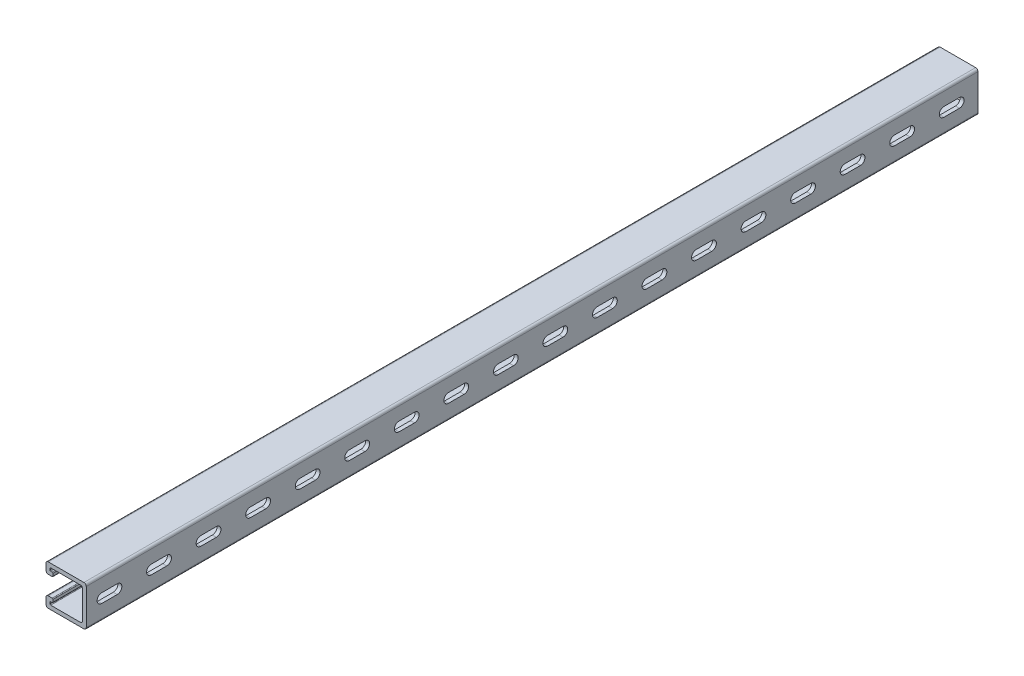
SolidWorks part; units mm, degrees
ref_plane "Front Plane" through (0, 0, 0) normal (0, 0, 1) x (1, 0, 0)
ref_plane "Top Plane" through (0, 0, 0) normal (0, 1, 0) x (1, 0, 0)
ref_plane "Right Plane" through (0, 0, 0) normal (1, 0, 0) x (0, 0, -1)
sketch "Sketch1" plane through (0, 0, 0) normal (0, 0, 1) x (1, 0, 0)
  line L0 (-13.5255, 9.525) -> (-18.2499, 9.525)
  line L1 (-20.6375, 11.9126) -> (-20.6375, 18.2499)
  line L2 (-18.2499, 20.6375) -> (18.2499, 20.6375)
  line L3 (20.6375, 18.2499) -> (20.6375, -18.2499)
  line L4 (18.2499, -20.6375) -> (-18.2499, -20.6375)
  line L5 (-20.6375, -18.2499) -> (-20.6375, -11.9126)
  line L6 (-18.2499, -9.525) -> (-13.5255, -9.525)
  line L7 (0, 0) -> (20.6375, 0) construction
  line L8 (0, 0) -> (0, 20.6375) construction
  arc A0 (-20.6375, 18.2499) -> (-18.2499, 20.6375) centre (-18.2499, 18.2499) cw
  arc A1 (-18.2499, 9.525) -> (-20.6375, 11.9126) centre (-18.2499, 11.9126) cw
  arc A2 (-20.6375, -11.9126) -> (-18.2499, -9.525) centre (-18.2499, -11.9126) cw
  arc A3 (-18.2499, -20.6375) -> (-20.6375, -18.2499) centre (-18.2499, -18.2499) cw
  arc A4 (20.6375, -18.2499) -> (18.2499, -20.6375) centre (18.2499, -18.2499) cw
  arc A5 (18.2499, 20.6375) -> (20.6375, 18.2499) centre (18.2499, 18.2499) cw
  point P14 (-20.6375, 20.6375)
  point P23 (20.6375, -20.6375)
  point P26 (20.6375, 20.6375)
  dimension "D4" = 2.3876
  dimension "D1" = 41.275
  dimension "D2" = 41.275
  dimension "D3" = 19.05
  dimension "D5" = 7.112
extrude "Extrude-Thin1" add sketch "Sketch1" against normal blind 914.4 thin
fillet "Fillet2" radius 0.762 8 edges at (-16.5735, 13.589, -457.2) (-16.5735, -16.5735, -457.2) (-16.5735, 16.5735, -457.2) (-13.5255, 13.589, -457.2) (-13.5255, 9.525, -457.2) (-13.5255, -9.525, -457.2) (-13.5255, -13.589, -457.2) (-16.5735, -13.589, -457.2)
fillet "Fillet3" radius 1.524 2 edges at (16.5735, 16.5735, -457.2) (16.5735, -16.5735, -457.2)
sketch "Sketch2" plane through (20.6375, 0, 0) normal (1, 0, 0) x (0, 0, -1)
  line L0 (15.875, 0) -> (31.75, 0) construction
  line L1 (15.875, 4.7625) -> (31.75, 4.7625)
  line L2 (15.875, -4.7625) -> (31.75, -4.7625)
  line L4 (15.875, 0) -> (0, 0) construction
  line L5 (23.8125, 0) -> (74.6125, 0) construction
  line L6 (0, 18.2499) -> (0, -18.2499) construction
  arc A0 (15.875, 4.7625) -> (15.875, -4.7625) centre (15.875, 0) ccw
  arc A1 (31.75, -4.7625) -> (31.75, 4.7625) centre (31.75, 0) ccw
  point P2 (23.8125, 0)
  dimension "D1" = 9.525
  dimension "D2" = 25.4
  dimension "Center Length" = 50.8
  dimension "D3" = 11.1125
extrude "Cut-Extrude1" cut sketch "Sketch2" against normal through all
pattern_linear "LPattern1" count 18 spacing 50.8 along (0, 0, -1) of "Cut-Extrude1"
sketch "Sketch3" plane through (0, 0, 0) normal (1, 0, 0) x (0, 0, -1)
  line L0 (0, 0) -> (914.4, 0) construction
  line L1 (914.4, 18.2499) -> (914.4, -18.2499) construction
  point P3 (101.6, 0)
  point P4 (812.8, 0)
  dimension "D1" = 101.6
  dimension "D2" = 101.6
equation "\"D3@LPattern1\" = \"Center Length@Sketch2\""
equation "\"D1@LPattern1\" = \"Length@Extrude-Thin1\"/\"Center Length@Sketch2\""
